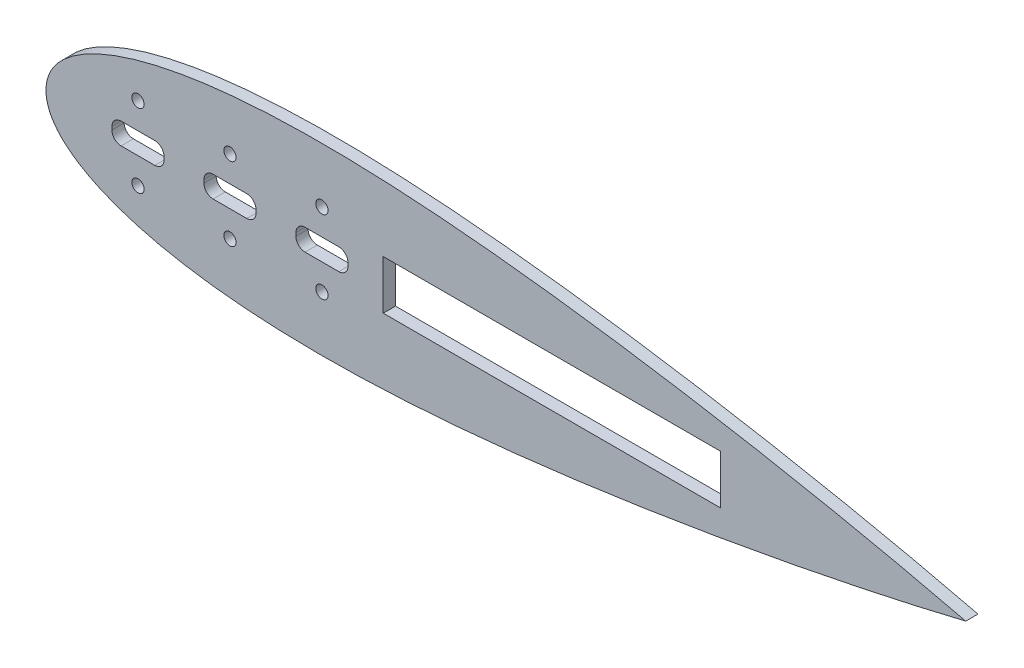
SolidWorks part; units mm, degrees
ref_plane "前视基准面" through (0, 0, 0) normal (0, 0, 1) x (1, 0, 0)
ref_plane "上视基准面" through (0, 0, 0) normal (0, 1, 0) x (1, 0, 0)
ref_plane "右视基准面" through (0, 0, 0) normal (1, 0, 0) x (0, 0, -1)
sketch "草图1" plane through (0, 0, 0) normal (0, 0, 1) x (1, 0, 0)
  line L0 (54.5, 3.5) -> (65.5, 3.5)
  line L1 (24.5, 3.5) -> (35.5, 3.5)
  line L2 (21.5, 0.5) -> (21.5, -0.5)
  line L3 (24.5, -3.5) -> (35.5, -3.5)
  line L4 (38.5, 0.5) -> (38.5, -0.5)
  line L5 (21.5, 3.5) -> (38.5, -3.5) construction
  line L6 (21.5, -3.5) -> (38.5, 3.5) construction
  line L7 (51.5, 0.5) -> (51.5, -0.5)
  line L8 (54.5, -3.5) -> (65.5, -3.5)
  line L9 (68.5, 0.5) -> (68.5, -0.5)
  line L10 (51.5, 3.5) -> (68.5, -3.5) construction
  line L11 (51.5, -3.5) -> (68.5, 3.5) construction
  line L12 (84.5, 3.5) -> (95.5, 3.5)
  line L13 (81.5, 0.5) -> (81.5, -0.5)
  line L14 (84.5, -3.5) -> (95.5, -3.5)
  line L15 (98.5, 0.5) -> (98.5, -0.5)
  line L16 (81.5, 3.5) -> (98.5, -3.5) construction
  line L17 (81.5, -3.5) -> (98.5, 3.5) construction
  line L19 (110, 8) -> (220, 8)
  line L20 (110, 8) -> (110, -8)
  line L21 (110, -8) -> (220, -8)
  line L22 (220, 8) -> (220, -8)
  line L23 (110, 8) -> (220, -8) construction
  line L24 (110, -8) -> (220, 8) construction
  arc A0 (35.5, 3.5) -> (38.5, 0.5) centre (35.5, 0.5) cw
  arc A1 (24.5, 3.5) -> (21.5, 0.5) centre (24.5, 0.5) ccw
  arc A2 (21.5, -0.5) -> (24.5, -3.5) centre (24.5, -0.5) ccw
  arc A3 (35.5, -3.5) -> (38.5, -0.5) centre (35.5, -0.5) ccw
  arc A4 (65.5, 3.5) -> (68.5, 0.5) centre (65.5, 0.5) cw
  arc A5 (54.5, 3.5) -> (51.5, 0.5) centre (54.5, 0.5) ccw
  arc A6 (51.5, -0.5) -> (54.5, -3.5) centre (54.5, -0.5) ccw
  arc A7 (65.5, -3.5) -> (68.5, -0.5) centre (65.5, -0.5) ccw
  arc A8 (95.5, 3.5) -> (98.5, 0.5) centre (95.5, 0.5) cw
  arc A9 (84.5, 3.5) -> (81.5, 0.5) centre (84.5, 0.5) ccw
  arc A10 (81.5, -0.5) -> (84.5, -3.5) centre (84.5, -0.5) ccw
  arc A11 (95.5, -3.5) -> (98.5, -0.5) centre (95.5, -0.5) ccw
  circle A12 centre (30, 12) radius 2
  circle A13 centre (30, -12) radius 2
  circle A14 centre (60, 12) radius 2
  circle A15 centre (60, -12) radius 2
  circle A16 centre (90, 12) radius 2
  circle A17 centre (90, -12) radius 2
  spline S0 degree 4 poles (0, 0) (-0.0002, 0.507) (0.0449, 1.3817) (0.226, 2.6508) (0.688, 4.3) (1.3355, 5.873) (2.267, 7.5426) (3.5719, 9.3461) (5.3914, 11.3247) (7.9545, 13.5395) (11.585, 16.0215) (16.6481, 18.727) (23.7932, 21.6498) (33.0858, 24.4369) (46.6431, 27.2845) (64.0632, 29.3627) (84.4508, 30.2603) (107.4149, 29.86) (130.3326, 28.4283) (153.1861, 26.2148) (175.9708, 23.3917) (195.8486, 20.4876) (212.8449, 17.733) (226.9805, 15.2709) (238.2713, 13.2039) (248.1352, 11.3101) (256.5773, 9.6255) (263.6047, 8.1795) (269.2198, 6.9974) (274.131, 5.9394) (278.332, 5.0171) (281.8385, 4.235) (284.6266, 3.6061) (287.4466, 2.9621) (290.2003, 2.3266) (293.0761, 1.6538) (295.7002, 1.0342) (299.1487, 0.2076) (301.6998, -0.4115) (305.9289, -1.45) (309.2336, -2.281) (313.2598, -3.3026) (316.8434, -4.2332) (320.6976, -5.2459) (323.9028, -6.1065) (326.7456, -6.8783) (328.5968, -7.3881) (329.5319, -7.6468) (330.0005, -7.7768) knots 0 0 0 0 0 0.005875 0.010168 0.014828 0.019835 0.025575 0.032309 0.04061 0.050967 0.064812 0.083253 0.107121 0.14043 0.177264 0.243882 0.3105 0.377118 0.443736 0.510354 0.576972 0.64359 0.676899 0.710208 0.743517 0.776826 0.793481 0.810135 0.82679 0.843444 0.851772 0.860099 0.868426 0.876753 0.885081 0.893408 0.901735 0.910062 0.921305 0.932547 0.943789 0.955031 0.966273 0.977516 0.988758 0.994379 1 1 1 1 1 construction
  spline S1 degree 4 poles (0, 0) (-0.0002, 0.507) (0.0449, 1.3817) (0.226, 2.6508) (0.688, 4.3) (1.3355, 5.873) (2.267, 7.5426) (3.5719, 9.3461) (5.3914, 11.3247) (7.9545, 13.5395) (11.585, 16.0215) (16.6481, 18.727) (23.7932, 21.6498) (33.0858, 24.4369) (46.6431, 27.2845) (64.0632, 29.3627) (84.4508, 30.2603) (107.4149, 29.86) (130.3326, 28.4283) (153.1861, 26.2148) (175.9708, 23.3917) (195.8486, 20.4876) (212.8449, 17.733) (226.9805, 15.2709) (238.2713, 13.2039) (248.1352, 11.3101) (256.5773, 9.6255) (263.6047, 8.1795) (269.2198, 6.9974) (274.131, 5.9394) (278.332, 5.0171) (281.8385, 4.235) (284.6266, 3.6061) (287.4466, 2.9621) (290.2003, 2.3266) (293.0761, 1.6538) (295.7002, 1.0342) (298.0785, 0.4641) (299.3655, 0.1537) (300, 0) knots 0 0 0 0 0 0.005875 0.010168 0.014828 0.019835 0.025575 0.032309 0.04061 0.050967 0.064812 0.083253 0.107121 0.14043 0.177264 0.243882 0.3105 0.377118 0.443736 0.510354 0.576972 0.64359 0.676899 0.710208 0.743517 0.776826 0.793481 0.810135 0.82679 0.843444 0.851772 0.860099 0.868426 0.876753 0.885081 0.893408 0.901735 0.910062 0.910062 0.910062 0.910062 0.910062
  spline S2 degree 4 poles (0, 0) (-0.0002, -0.507) (0.0449, -1.3817) (0.226, -2.6508) (0.688, -4.3) (1.3355, -5.873) (2.267, -7.5426) (3.5719, -9.3461) (5.3914, -11.3247) (7.9545, -13.5395) (11.585, -16.0215) (16.6481, -18.727) (23.7932, -21.6498) (33.0858, -24.4369) (46.6431, -27.2845) (64.0632, -29.3627) (84.4508, -30.2603) (107.4149, -29.86) (130.3326, -28.4283) (153.1861, -26.2148) (175.9708, -23.3917) (195.8486, -20.4876) (212.8449, -17.733) (226.9805, -15.2709) (238.2713, -13.2039) (248.1352, -11.3101) (256.5773, -9.6255) (263.6047, -8.1795) (269.2198, -6.9974) (274.131, -5.9394) (278.332, -5.0171) (281.8385, -4.235) (284.6266, -3.6061) (287.4466, -2.9621) (290.2003, -2.3266) (293.0761, -1.6538) (295.7002, -1.0342) (299.1487, -0.2076) (301.6998, 0.4115) (305.9289, 1.45) (309.2336, 2.281) (313.2598, 3.3026) (316.8434, 4.2332) (320.6976, 5.2459) (323.9028, 6.1065) (326.7456, 6.8783) (328.5968, 7.3881) (329.5319, 7.6468) (330.0005, 7.7768) knots 0 0 0 0 0 0.005875 0.010168 0.014828 0.019835 0.025575 0.032309 0.04061 0.050967 0.064812 0.083253 0.107121 0.14043 0.177264 0.243882 0.3105 0.377118 0.443736 0.510354 0.576972 0.64359 0.676899 0.710208 0.743517 0.776826 0.793481 0.810135 0.82679 0.843444 0.851772 0.860099 0.868426 0.876753 0.885081 0.893408 0.901735 0.910062 0.921305 0.932547 0.943789 0.955031 0.966273 0.977516 0.988758 0.994379 1 1 1 1 1 construction
  spline S3 degree 4 poles (0, 0) (-0.0002, -0.507) (0.0449, -1.3817) (0.226, -2.6508) (0.688, -4.3) (1.3355, -5.873) (2.267, -7.5426) (3.5719, -9.3461) (5.3914, -11.3247) (7.9545, -13.5395) (11.585, -16.0215) (16.6481, -18.727) (23.7932, -21.6498) (33.0858, -24.4369) (46.6431, -27.2845) (64.0632, -29.3627) (84.4508, -30.2603) (107.4149, -29.86) (130.3326, -28.4283) (153.1861, -26.2148) (175.9708, -23.3917) (195.8486, -20.4876) (212.8449, -17.733) (226.9805, -15.2709) (238.2713, -13.2039) (248.1352, -11.3101) (256.5773, -9.6255) (263.6047, -8.1795) (269.2198, -6.9974) (274.131, -5.9394) (278.332, -5.0171) (281.8385, -4.235) (284.6266, -3.6061) (287.4466, -2.9621) (290.2003, -2.3266) (293.0761, -1.6538) (295.7002, -1.0342) (298.0785, -0.4641) (299.3655, -0.1537) (300, 0) knots 0 0 0 0 0 0.005875 0.010168 0.014828 0.019835 0.025575 0.032309 0.04061 0.050967 0.064812 0.083253 0.107121 0.14043 0.177264 0.243882 0.3105 0.377118 0.443736 0.510354 0.576972 0.64359 0.676899 0.710208 0.743517 0.776826 0.793481 0.810135 0.82679 0.843444 0.851772 0.860099 0.868426 0.876753 0.885081 0.893408 0.901735 0.910062 0.910062 0.910062 0.910062 0.910062
  point P0 (30, 0)
  point P24 (60, 0)
  point P44 (90, 0)
  point P64 (165, 0)
  point P74 (0, 0)
  point P75 (0, 0)
  point P76 (0, 0)
  point P77 (0, 0)
  point P78 (0, 0)
  point P79 (0, 0)
  point P80 (0, 0)
  point P81 (0, 0)
  point P82 (0, 0)
  point P83 (0, 0)
  dimension "D1" = 3
  dimension "D2" = 3
  dimension "D3" = 3
  dimension "D4" = 3
  dimension "D7" = 3
  dimension "D8" = 3
  dimension "D9" = 3
  dimension "D10" = 3
  dimension "D13" = 3
  dimension "D14" = 3
  dimension "D15" = 3
  dimension "D16" = 3
  dimension "D5" = 11
  dimension "D6" = 1
  dimension "D11" = 11
  dimension "D12" = 1
  dimension "D17" = 11
  dimension "D18" = 1
extrude "凸台-拉伸1" add sketch "草图1" along normal blind 4
